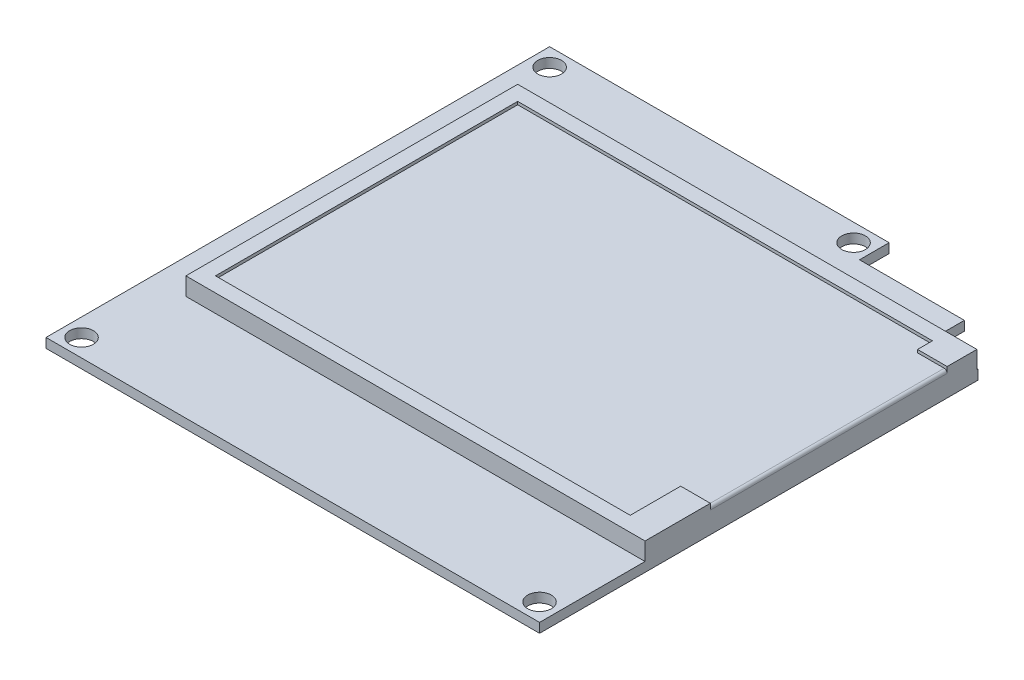
SolidWorks part; units mm, degrees
ref_plane "Plan de face" through (0, 0, 0) normal (0, 0, 1) x (1, 0, 0)
ref_plane "Plan de dessus" through (0, 0, 0) normal (0, 1, 0) x (1, 0, 0)
ref_plane "Plan de droite" through (0, 0, 0) normal (1, 0, 0) x (0, 0, -1)
sketch "Esquisse1" plane through (0, 0, 0) normal (0, 1, 0) x (1, 0, 0)
  line L0 (0, 0) -> (83.3, 0)
  line L1 (0, 0) -> (0, 85)
  line L2 (0, 85) -> (57.3, 85)
  line L3 (83.3, 0) -> (83.3, 74)
  line L4 (57.3, 85) -> (57.3, 80)
  line L5 (57.3, 80) -> (75, 80)
  line L6 (75, 80) -> (75, 74)
  line L7 (75, 74) -> (83.3, 74)
  dimension "D1" = 83.3
  dimension "D2" = 85
  dimension "D3" = 57.3
  dimension "D4" = 74
  dimension "D5" = 5
  dimension "D6" = 17.7
extrude "Boss.-Extru.1" add sketch "Esquisse1" along normal blind 1.6
sketch "Esquisse5" plane through (0, 1.6, 0) normal (0, 1, 0) x (1, 0, 0)
  line L0 (57.3, 85) -> (54.3, 85) construction
  line L1 (57.3, 85) -> (0, 85) construction
  line L2 (54.3, 85) -> (54.3, 82) construction
  line L3 (0, 85) -> (3, 85) construction
  line L4 (3, 85) -> (3, 82) construction
  line L5 (0, 0) -> (3, 0) construction
  line L6 (0, 0) -> (83.3, 0) construction
  line L7 (3, 0) -> (3, 2.997) construction
  line L8 (83.3, 0) -> (83.3, 2.997) construction
  line L9 (83.3, 0) -> (83.3, 74) construction
  line L10 (83.3, 2.997) -> (80.2983, 2.997) construction
  circle A0 centre (54.3, 82) radius 2
  circle A1 centre (3, 82) radius 2
  circle A2 centre (3, 2.997) radius 2
  circle A3 centre (80.2983, 2.997) radius 2
  dimension "D2" = 3
  dimension "D1" = 3
  dimension "D3" = 3
  dimension "D4" = 3
extrude "Enlèv. mat.-Extru.1" cut sketch "Esquisse5" against normal blind 1.6
sketch "ecran" plane through (0, 1.6, 0) normal (0, 1, 0) x (1, 0, 0)
  line L0 (83.3, 73.8084) -> (5.8019, 73.8084) construction
  line L1 (83.3, 0) -> (83.3, 74) construction
  line L2 (5.8019, 73.8084) -> (5.8019, 17.8043) construction
  line L3 (5.8019, 17.8043) -> (83.3, 17.8043) construction
  line L4 (83.3, 17.8043) -> (83.3, 73.8084) construction
  line L6 (5.8019, 73.8084) -> (83.3, 73.8084)
  line L7 (5.8019, 73.8084) -> (5.8019, 17.8043)
  line L8 (5.8019, 17.8043) -> (83.3, 17.8043)
  line L9 (83.3, 73.8084) -> (83.3, 17.8043)
extrude "Boss.-Extru.2" add sketch "ecran" along normal blind 3
sketch "ecran noir" plane through (0, 4.6, 0) normal (0, 1, 0) x (1, 0, 0)
  line L0 (5.8019, 73.8084) -> (8.2985, 73.8084) construction
  line L1 (83.3, 73.8084) -> (5.8019, 73.8084) construction
  line L2 (8.2985, 73.8084) -> (8.2985, 71.3111) construction
  line L3 (83.3, 73.8084) -> (83.3, 71.3111) construction
  line L4 (83.3, 17.8043) -> (83.3, 73.8084) construction
  line L5 (83.3, 71.3111) -> (78.2993, 71.3111) construction
  line L6 (78.2993, 17.8043) -> (78.2993, 20.3066) construction
  line L7 (5.8019, 17.8043) -> (83.3, 17.8043) construction
  line L9 (78.2993, 20.3066) -> (8.2985, 20.3066)
  line L10 (78.2993, 20.3066) -> (78.2993, 71.3111)
  line L11 (78.2993, 71.3111) -> (8.2985, 71.3111)
  line L12 (8.2985, 20.3066) -> (8.2985, 71.3111)
extrude "Enlèv. mat.-Extru.2" cut sketch "ecran noir" against normal blind 0.5
sketch "nappe contacteurs" plane through (0, 4.6, 0) normal (0, 1, 0) x (1, 0, 0)
  line L0 (83.3, 73.8084) -> (83.3, 68.7958) construction
  line L1 (83.3, 17.8043) -> (83.3, 73.8084) construction
  line L2 (83.3, 17.8043) -> (83.3, 28.8232) construction
  line L3 (78.2993, 20.3066) -> (78.2993, 71.3111) construction
  line L4 (83.3, 68.7958) -> (78.2993, 68.7958)
  line L5 (83.3, 68.7958) -> (83.3, 28.8232)
  line L6 (83.3, 28.8232) -> (78.2993, 28.8232)
  line L7 (78.2993, 68.7958) -> (78.2993, 28.8232)
extrude "Enlèv. mat.-Extru.3" cut sketch "nappe contacteurs" against normal blind 0.5
fillet "Congé1" radius 0.5 1 edges at (83.3, 4.1, -48.8095)
